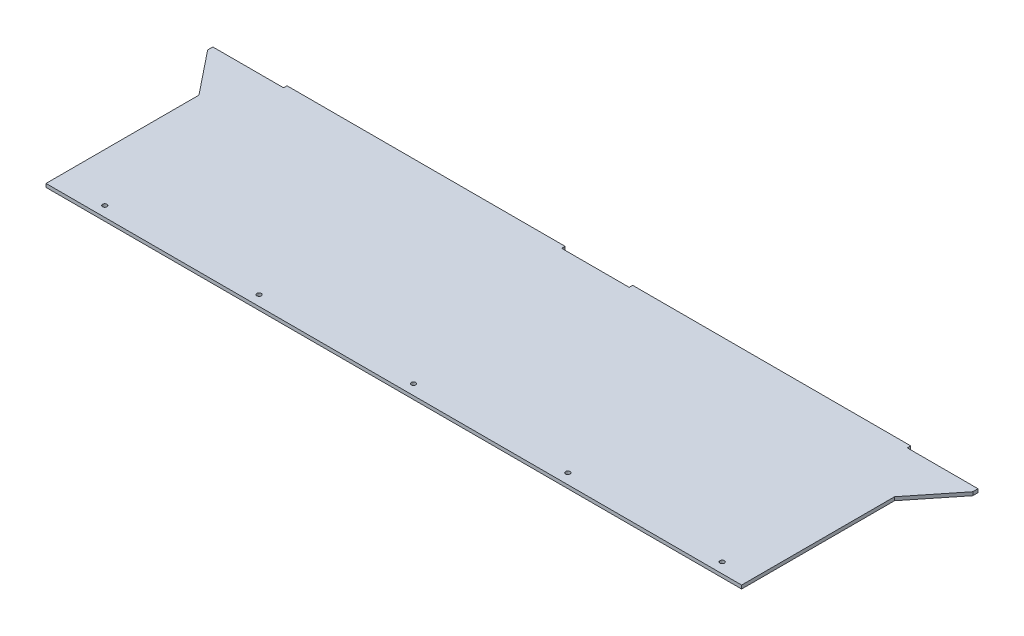
SolidWorks part; units mm, degrees
material "6061-T6 (SS)"
ref_plane "X-Y Datum" through (0, 0, 0) normal (0, 0, 1) x (1, 0, 0)
ref_plane "X-Z Datum" through (0, 0, 0) normal (0, 1, 0) x (1, 0, 0)
ref_plane "Y-Z Datum" through (0, 0, 0) normal (1, 0, 0) x (0, 0, -1)
sketch "Sketch1" plane through (0, 0, 0) normal (0, 1, 0) x (1, 0, 0)
  line L1 (-317.6778, 92.075) -> (317.6778, 92.075)
  line L2 (-317.6778, 92.075) -> (-317.6778, -92.075)
  line L3 (-317.6778, -92.075) -> (317.6778, -92.075)
  line L4 (317.6778, 92.075) -> (317.6778, -92.075)
  line L5 (-317.6778, 92.075) -> (317.6778, -92.075) construction
  line L6 (-317.6778, -92.075) -> (317.6778, 92.075) construction
  point P0 (0, 0)
  dimension "D1" = 635.3556
  dimension "D2" = 184.15
extrude "Boss-Extrude1" add sketch "Sketch1" along normal mid plane 3.175
sketch "Sketch2" plane through (0, 0, -92.075) normal (0, 0, -1) x (-1, 0, 0)
  line L20 (-317.6778, -1.5875) -> (317.6778, -1.5875) construction
  line L21 (-284.8229, -1.5875) -> (-30.8229, -1.5875)
  line L22 (30.8229, -1.5875) -> (284.8229, -1.5875)
  line L40 (30.8229, -1.5875) -> (30.8229, 1.5875)
  line L41 (30.8229, 1.5875) -> (284.8229, 1.5875)
  line L42 (284.8229, 1.5875) -> (284.8229, -1.5875)
  line L56 (-284.8229, -1.5875) -> (-284.8229, 1.5875)
  line L57 (-284.8229, 1.5875) -> (-30.8229, 1.5875)
  line L58 (-30.8229, 1.5875) -> (-30.8229, -1.5875)
extrude "Boss-Extrude2" add sketch "Sketch2" along normal blind 3.175
sketch "Sketch3" plane through (0, -1.5875, 0) normal (0, -1, 0) x (1, 0, 0)
  line L0 (317.6778, -92.075) -> (349.4278, -92.075)
  line L1 (349.4278, -92.075) -> (349.4278, -87.3125)
  line L3 (349.4278, -87.3125) -> (317.6778, -47.625)
  line L4 (317.6778, 92.075) -> (317.6778, -92.075) construction
  line L17 (317.6778, -92.075) -> (317.6778, 92.075)
  line L18 (317.6778, 92.075) -> (-317.6778, 92.075)
  line L19 (-317.6778, 92.075) -> (-317.6778, -92.075)
  line L20 (-317.6778, -92.075) -> (-284.8229, -92.075)
  line L21 (-284.8229, -92.075) -> (-284.8229, -95.25)
  line L22 (-284.8229, -95.25) -> (-30.8229, -95.25)
  line L23 (-30.8229, -95.25) -> (-30.8229, -92.075)
  line L24 (-30.8229, -92.075) -> (30.8229, -92.075)
  line L25 (30.8229, -92.075) -> (30.8229, -95.25)
  line L26 (30.8229, -95.25) -> (284.8229, -95.25)
  line L27 (284.8229, -95.25) -> (284.8229, -92.075)
  line L28 (284.8229, -92.075) -> (317.6778, -92.075)
  line L29 (317.6778, -92.075) -> (317.6778, -47.625)
  dimension "D1" = 31.75
  dimension "D2" = 4.7625
  dimension "D3" = 44.45
  dimension "D4" = 0
extrude "Boss-Extrude3" add sketch "Sketch3" against normal blind 3.175
mirror "Mirror1" about plane through (0, 0, 0) normal (1, 0, 0) of "Boss-Extrude3"
sketch "Sketch4" plane through (0, 1.5875, 0) normal (0, 1, 0) x (1, 0, 0)
  line L0 (290.4998, -92.075) -> (290.4998, -82.677)
  line L1 (-317.6778, -92.075) -> (317.6778, -92.075) construction
  line L2 (290.4998, -82.677) -> (317.6778, -82.677)
  line L3 (317.6778, -92.075) -> (317.6778, 47.625) construction
  circle A0 centre (290.4998, -82.677) radius 2.025
extrude "Cut-Extrude1" cut sketch "Sketch4" against normal blind 10 contours L2 A0 L0 | L0 A0 L2
pattern_linear "LPattern1" count 5 spacing 140.97 along (-1, 0, 0) of "Cut-Extrude1"
